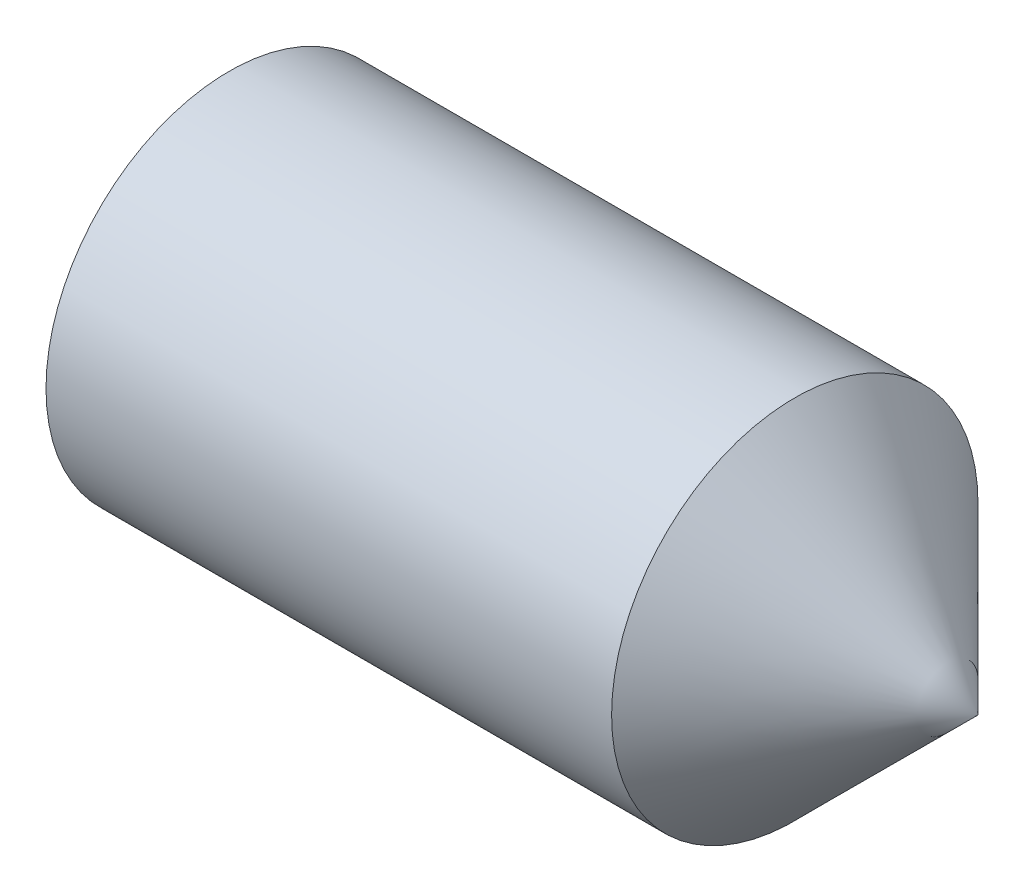
SolidWorks part; units mm, degrees
revolve "BaseBody" add sketch "BodySke" angle 360 about L5
sketch "BodySke" plane through (0, 0, 0) normal (0, 0, 1) x (1, 0, 0)
  line L0 (0, 0) -> (0, 10.352)
  line L1 (0, 10.352) -> (0.9515, 12)
  line L2 (0.9515, 12) -> (38, 12)
  line L3 (38, 12) -> (50, 0)
  line L4 (50, 0) -> (0, 0)
  line L5 (-12.7, 0) -> (88.9, 0) construction
  line L6 (38, -12) -> (50, 0) construction
  line L7 (1.5, 15.875) -> (1.5, -3.175) construction
  line L8 (0, -10.352) -> (0.9515, -12) construction
  dimension "Diameter" = 24
  dimension "Drive_ch_ang" = 60
  dimension "Minor_dia" = 20.704
  dimension "Advance" = 3
  dimension "Cone_ang" = 90
  dimension "Length" = 50
cosmetic thread "ThreadCosmetic" [suppressed] parameters "Thread_minor"=20.704
ref_plane "Plane1" through (0, 0, 0) normal (0, 0, 1) x (1, 0, 0)
ref_plane "Plane2" through (0, 0, 0) normal (0, 1, 0) x (1, 0, 0)
ref_plane "Plane3" through (0, 0, 0) normal (1, 0, 0) x (0, 0, -1)
sketch "Sketch2" plane through (0, 0, 0) normal (-1, 0, 0) x (0, 0, 1)
  line L0 (3.4641, 6) -> (-3.4641, 6)
  line L1 (-3.4641, 6) -> (-6.9282, 0)
  line L2 (3.4641, 6) -> (6.9282, 0)
  line L3 (3.4641, -6) -> (6.9282, 0)
  line L4 (3.4641, -6) -> (-3.4641, -6)
  line L5 (-3.4641, -6) -> (-6.9282, 0)
  dimension "Hex_size" = 12
  dimension "D2" = 6
  dimension "D3" = 6
extrude "Hex" cut sketch "Sketch2" against normal blind 15
sketch "ThdSchSke" plane through (0, 0, 0) normal (0, 0, 1) x (1, 0, 0)
  line L0 (0.9515, -10.352) -> (-0.2025, -12)
  line L1 (0.9515, -10.352) -> (2.1054, -12)
  line L2 (2.1054, -12) -> (2.1054, -15)
  line L3 (-3.175, 0) -> (5.1513, 0) construction
  line L4 (0.9515, 12) -> (0.9515, -12) construction
  line L5 (2.1054, -15) -> (-0.2025, -15)
  line L6 (-0.2025, -15) -> (-0.2025, -12)
  dimension "Thread_minor" = 20.704
  dimension "Diameter" = 24
revolve "ThreadSchematic" [suppressed] cut sketch "ThdSchSke" angle 360 about L3
pattern_linear "ThdSchPat" [suppressed]
equation "\"D2@Sketch2\" = \"Hex_size@Sketch2\" / 2"
equation "\"D3@Sketch2\" = \"Hex_size@Sketch2\" / 2"
equation "\"Thread_minor@ThreadCosmetic\" = \"Minor_dia@BodySke\""
equation "\"Thread_minor@ThdSchSke\" = \"Thread_minor@ThreadCosmetic\""
equation "\"Diameter@ThdSchSke\" = \"Diameter@BodySke\""
equation "\"Overcut@ThdSchSke\" = \"Diameter@BodySke\" * 1.25"
equation "\"Num_threads@ThdSchPat\" = int( (\"Length@BodySke\" - ( ( ( \"Diameter@BodySke\" - \"Minor_dia@BodySke\" ) * 0.5 ) / tan( \"Drive_ch_ang@BodySke\" * 0.017453292 ) ) - ( ( \"Diameter@BodySke\" * 0.5 ) / tan( \"Cone_ang@BodySke\" * 0.008726646 ) ) ) / \"Advance@BodySke\" + 0.999 )  + 1"
equation "\"Advance@ThdSchPat\" = (\"Length@BodySke\" - ( ( ( \"Diameter@BodySke\" - \"Minor_dia@BodySke\" ) * 0.5 ) / tan( \"Drive_ch_ang@BodySke\" * 0.017453292 ) ) - ( ( \"Diameter@BodySke\" * 0.5 ) / tan( \"Cone_ang@BodySke\" * 0.008726646 ) ) ) /  (\"Num_threads@ThdSchPat\" - 1) 'relax it"
equation "' \"Num_threads@ThdSchPat\" = \"Num_threads@ThdSchPat\" - sgn( \"Num_threads@ThdSchPat\" - 1) '---chamfered tips only---"
